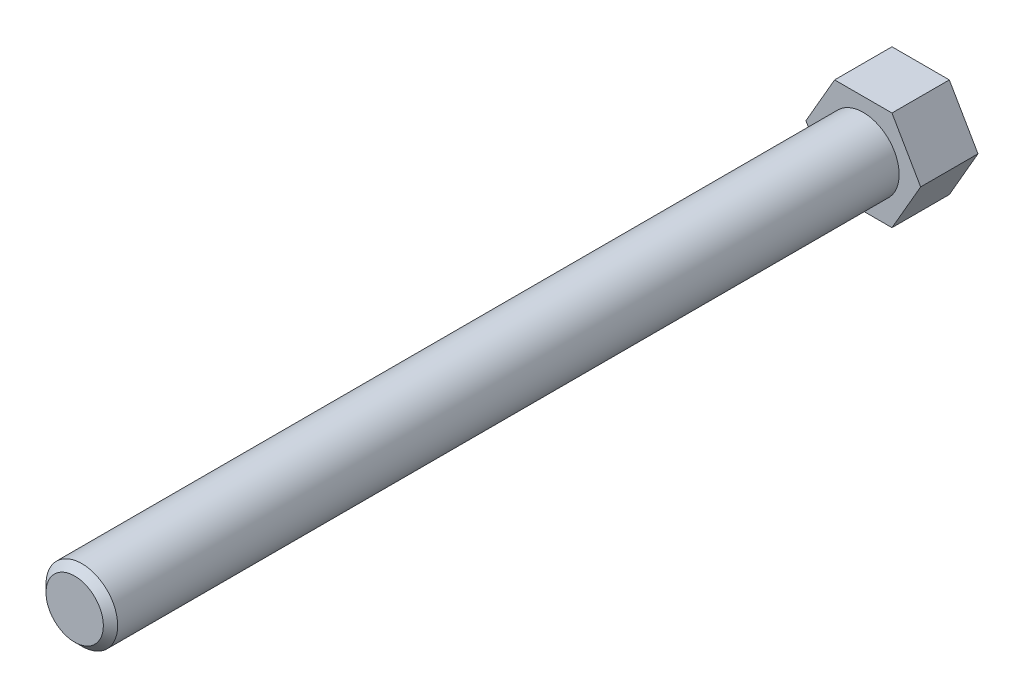
SolidWorks part; units mm, degrees
ref_plane "前视基准面" through (0, 0, 0) normal (0, 0, 1) x (1, 0, 0)
ref_plane "上视基准面" through (0, 0, 0) normal (0, 1, 0) x (1, 0, 0)
ref_plane "右视基准面" through (0, 0, 0) normal (1, 0, 0) x (0, 0, -1)
sketch "草图1" plane through (0, 0, 0) normal (0, 0, 1) x (1, 0, 0)
  circle A0 centre (0, 0) radius 2.5
  dimension "D1" = 5
extrude "拉伸1" add sketch "草图1" along normal blind 55
cosmetic thread "装饰螺纹线2" parameters "D1"=30, "D2"=4.2
sketch "草图2" plane through (0, 0, 0) normal (0, 0, 1) x (1, 0, 0)
  line L1 (2, -3.4641) -> (4, 0)
  line L2 (4, 0) -> (2, 3.4641)
  line L3 (2, 3.4641) -> (-2, 3.4641)
  line L4 (-2, 3.4641) -> (-4, 0)
  line L5 (-4, 0) -> (-2, -3.4641)
  line L6 (-2, -3.4641) -> (2, -3.4641)
  circle A0 centre (0, 0) radius 4 construction
  dimension "D1" = 4
extrude "拉伸2" add sketch "草图2" against normal blind 4
chamfer "倒角1" distance 0.5 angle 45 1 edges at (2.5, 0, 55)
